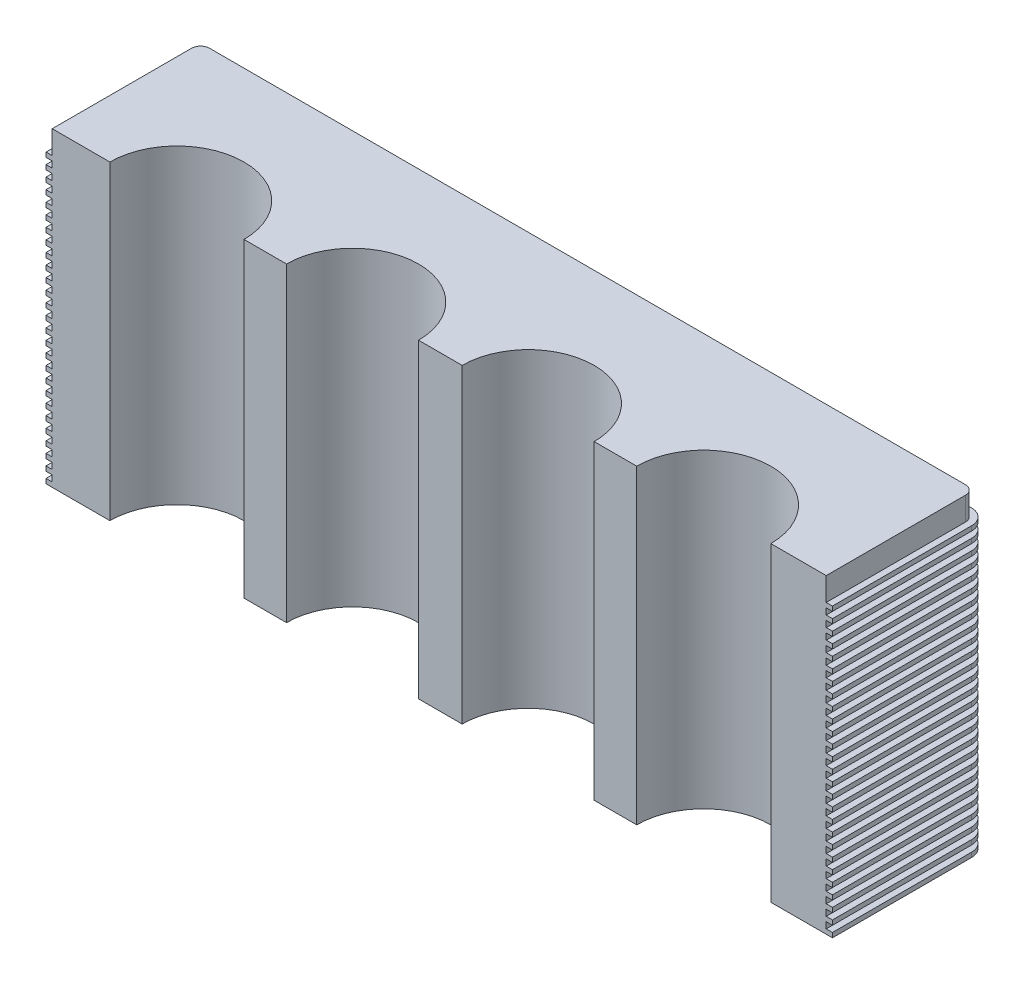
SolidWorks part; units mm, degrees
ref_plane "Front Plane" through (0, 0, 0) normal (0, 0, 1) x (1, 0, 0)
ref_plane "Top Plane" through (0, 0, 0) normal (0, 1, 0) x (1, 0, 0)
ref_plane "Right Plane" through (0, 0, 0) normal (1, 0, 0) x (0, 0, -1)
sketch "Sketch2" plane through (0, 0, 0) normal (0, 1, 0) x (1, 0, 0)
  line L6 (249.8812, 138.746) -> (249.8812, -20.1607) construction
  line L7 (0, 0) -> (37.1221, 0)
  line L8 (0, 0) -> (0, 89.6565)
  line L9 (5.8448, 95.5012) -> (492.4819, 95.5012)
  line L10 (498.3267, 0) -> (498.3267, 89.6565)
  line L11 (462.6403, 0) -> (498.3267, 0)
  line L12 (348.9207, 0) -> (376.2967, 0)
  line L13 (263.9207, 0) -> (249.8812, 0)
  line L14 (123.4656, 0) -> (150.8416, 0)
  line L15 (235.8416, 0) -> (249.8812, 0)
  arc A4 (0, 89.6565) -> (5.8448, 95.5012) centre (5.8448, 89.6565) cw
  arc A5 (492.4819, 95.5012) -> (498.3267, 89.6565) centre (492.4819, 89.6565) cw
  arc A6 (462.6403, 0) -> (376.2967, 0) centre (419.4685, 0) ccw
  arc A7 (348.9207, 0) -> (263.9207, 0) centre (306.4207, 0) ccw
  arc A8 (37.1221, 0) -> (123.4656, 0) centre (80.2938, 0) cw
  arc A9 (150.8416, 0) -> (235.8416, 0) centre (193.3416, 0) cw
  point P24 (498.3267, 0)
extrude "Boss-Extrude3" add sketch "Sketch2" along normal blind 200
sketch "Sketch5" plane through (0, 0, 0) normal (0, 1, 0) x (1, 0, 0)
  line L0 (502.3267, 0) -> (502.3267, 89.6565)
  line L1 (492.4819, 99.5012) -> (5.8448, 99.5012)
  line L2 (-4, 89.6565) -> (-4, 0)
  line L3 (498.3267, 0) -> (502.3267, 0)
  line L4 (0, 0) -> (-4, 0)
  line L8 (0, 89.6565) -> (0, 0)
  line L9 (0, 0) -> (37.1221, 0)
  line L10 (123.4656, 0) -> (150.8416, 0)
  line L11 (235.8416, 0) -> (263.9207, 0)
  line L12 (348.9207, 0) -> (376.2967, 0)
  line L13 (462.6403, 0) -> (498.3267, 0)
  line L14 (498.3267, 0) -> (498.3267, 89.6565)
  line L15 (492.4819, 95.5012) -> (5.8448, 95.5012)
  line L16 (0, 89.6565) -> (0, 0)
  line L22 (498.3267, 0) -> (498.3267, 89.6565)
  line L23 (492.4819, 95.5012) -> (5.8448, 95.5012)
  arc A0 (502.3267, 89.6565) -> (492.4819, 99.5012) centre (492.4819, 89.6565) ccw
  arc A1 (5.8448, 99.5012) -> (-4, 89.6565) centre (5.8448, 89.6565) ccw
  arc A6 (123.4656, 0) -> (37.1221, 0) centre (80.2938, 0) ccw
  arc A7 (235.8416, 0) -> (150.8416, 0) centre (193.3416, 0) ccw
  arc A8 (348.9207, 0) -> (263.9207, 0) centre (306.4207, 0) ccw
  arc A9 (462.6403, 0) -> (376.2967, 0) centre (419.4685, 0) ccw
  arc A10 (498.3267, 89.6565) -> (492.4819, 95.5012) centre (492.4819, 89.6565) ccw
  arc A11 (5.8448, 95.5012) -> (0, 89.6565) centre (5.8448, 89.6565) ccw
  arc A16 (498.3267, 89.6565) -> (492.4819, 95.5012) centre (492.4819, 89.6565) ccw
  arc A17 (5.8448, 95.5012) -> (0, 89.6565) centre (5.8448, 89.6565) ccw
  dimension "D1" = 0
  dimension "D2" = 4
extrude "Boss-Extrude4" add sketch "Sketch5" along normal blind 3
pattern_linear "LPattern1" count 27 spacing 7 along (0, 1, 0) of "Boss-Extrude4"
